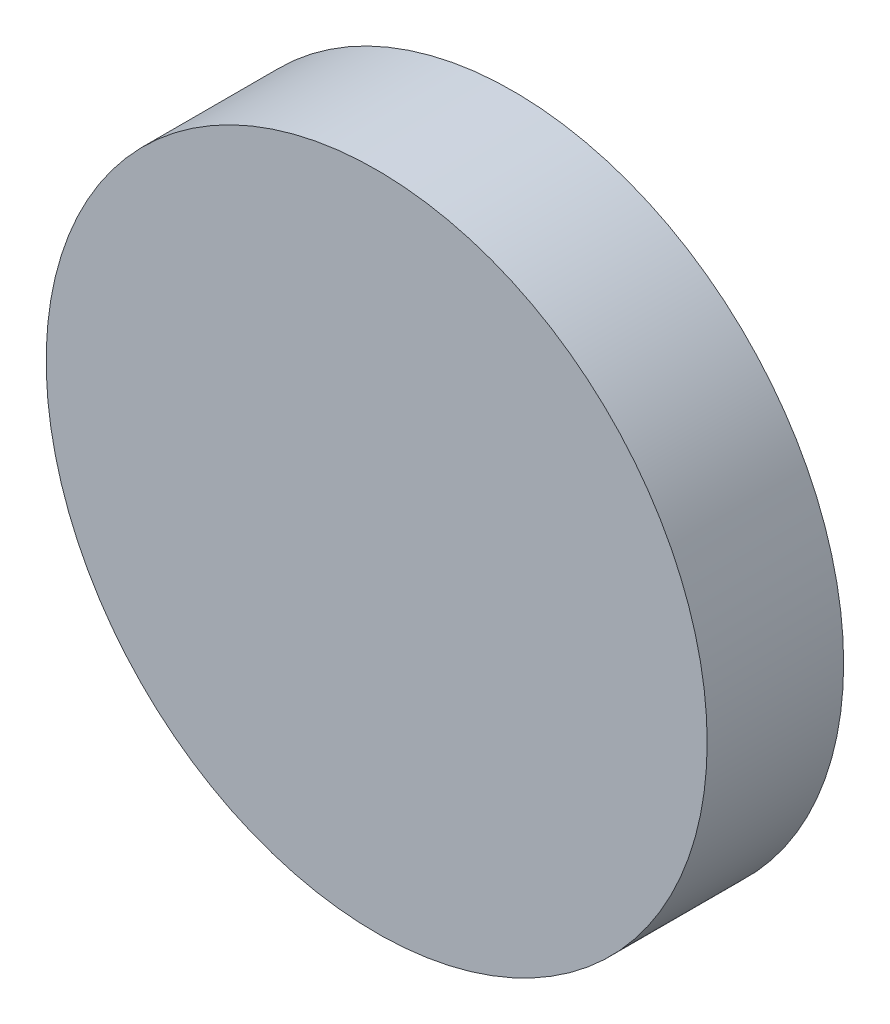
SolidWorks part; units mm, degrees
ref_plane "Front Plane" through (0, 0, 0) normal (0, 0, 1) x (1, 0, 0)
ref_plane "Top Plane" through (0, 0, 0) normal (0, 1, 0) x (1, 0, 0)
ref_plane "Right Plane" through (0, 0, 0) normal (1, 0, 0) x (0, 0, -1)
sketch "Sk_core" plane through (0, 0, 0) normal (0, 0, 1) x (1, 0, 0)
  circle A0 centre (38.481, -19.05) radius 38.4492
extrude "Ext_core" add sketch "Sk_core" along normal mid plane 15.875
